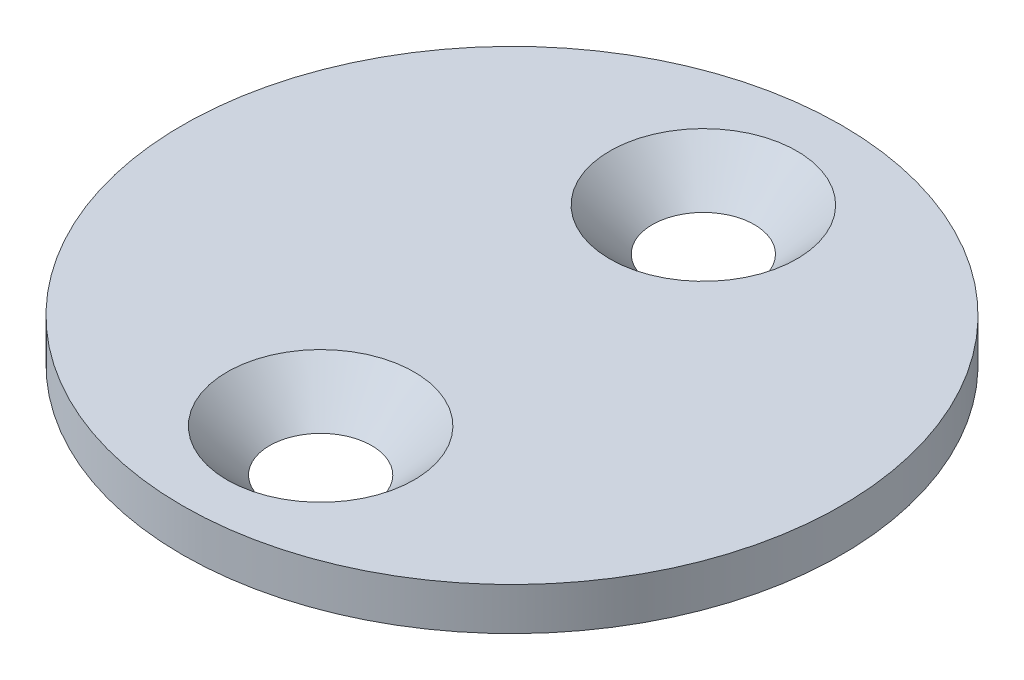
SolidWorks part; units mm, degrees
material "Brass"
ref_plane "Front" through (0, 0, 0) normal (0, 0, 1) x (1, 0, 0)
ref_plane "Top" through (0, 0, 0) normal (0, 1, 0) x (1, 0, 0)
ref_plane "Right" through (0, 0, 0) normal (1, 0, 0) x (0, 0, -1)
sketch "Sketch1" plane through (0, 0, 0) normal (0, 1, 0) x (1, 0, 0)
  circle A1 centre (0, 0) radius 7.75
  dimension "D2" = 15.5
extrude "Boss-Extrude1" add sketch "Sketch1" along normal blind 1
sketch "Sketch3" plane through (0, 1, 0) normal (0, 1, 0) x (1, 0, 0)
  line L0 (0, 7.75) -> (0, -7.75)
  circle A0 centre (0, 0) radius 7.75 construction
  circle A1 centre (0, -4.5) radius 0.5
  circle A2 centre (0, 4.5) radius 0.5
  point P7 (0, 0)
  dimension "D1" = 9
  dimension "D3" = 1
  dimension "D2" = 4.5
hole_wizard "CSK for M2 Flat Head Machine Screw3" positions "3DSketch4" profile "Sketch6" countersink size "M2" standard "ANSI Metric"
sketch3d "3DSketch4"
  point P0 (0, 1, 4.5)
  point P3 (0, 1, -4.5)
sketch "Sketch6" plane through (0, 1, 4.5) normal (1, 0, 0) x (0, 0, 1)
  line L0 (0, 0) -> (0, 2.721)
  line L1 (0, 2.721) -> (1.2, 2)
  line L2 (1.2, 2) -> (1.2, 1)
  line L3 (1.2, 1) -> (2.2, 0)
  line L5 (2.2, 0) -> (0, 0)
  line L6 (-1.2, 1) -> (-2.2, 0) construction
  line L10 (0, 2.721) -> (-1.2, 2) construction
  line L11 (0, -6.35) -> (0, 107.95) construction
  dimension "Hole Dia." = 2.4
  dimension "Hole Depth" = 2
  dimension "Near C'Sink Dia." = 4.4
  dimension "Near C'Sink Angle" = 90
  dimension "Drill Angle" = 118
